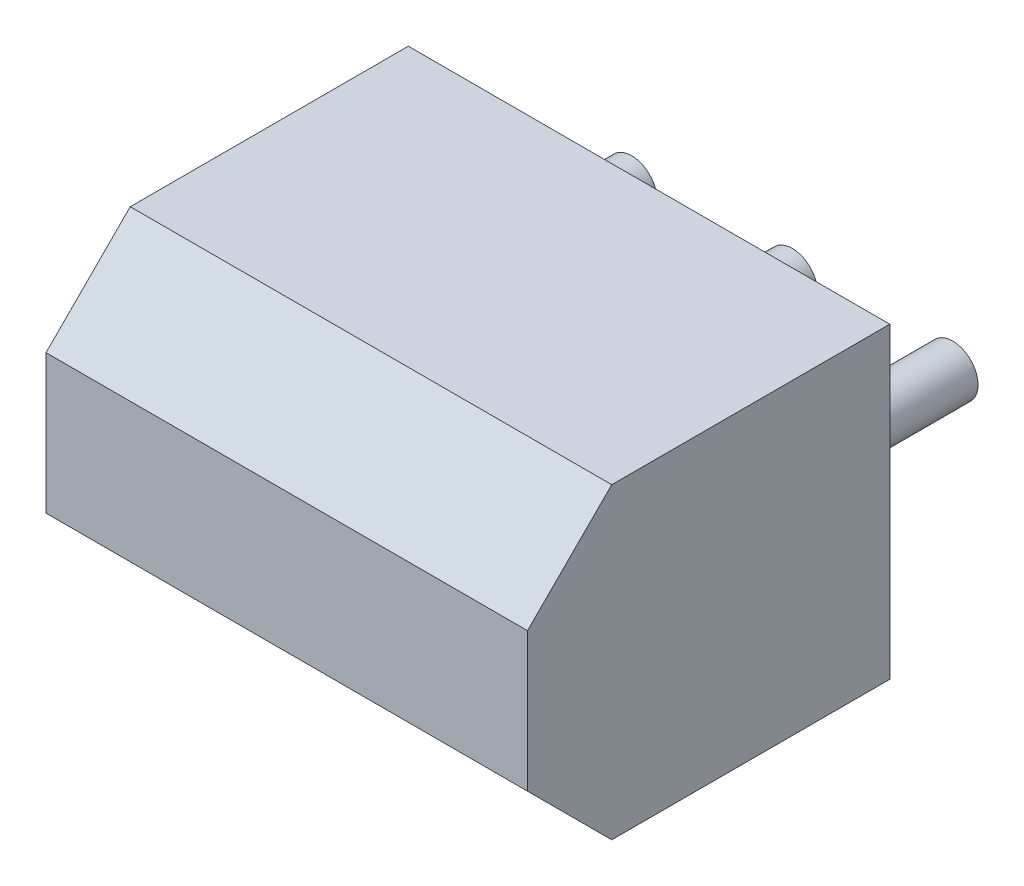
SolidWorks part; units mm, degrees
ref_plane "前视基准面" through (0, 0, 0) normal (0, 0, 1) x (1, 0, 0)
ref_plane "上视基准面" through (0, 0, 0) normal (0, 1, 0) x (1, 0, 0)
ref_plane "右视基准面" through (0, 0, 0) normal (1, 0, 0) x (0, 0, -1)
sketch "草图1" plane through (0, 0, 0) normal (0, 0, 1) x (1, 0, 0)
  line L1 (0, 0) -> (11.43, 0)
  line L2 (0, 0) -> (0, 7.3)
  line L3 (0, 7.3) -> (11.43, 7.3)
  line L4 (11.43, 0) -> (11.43, 7.3)
  dimension "D1" = 11.43
  dimension "D2" = 7.3
extrude "凸台-拉伸1" add sketch "草图1" along normal blind 8.6
chamfer "倒角1" distance 2 angle 45 2 edges at (5.715, 0, 8.6) (5.715, 7.3, 8.6)
sketch "草图2" plane through (0, 0, 0) normal (0, -1, 0) x (1, 0, 0)
  line L1 (4.965, 4.7244) -> (6.465, 4.7244)
  line L2 (4.965, 4.7244) -> (4.965, 2.4797)
  line L3 (4.965, 2.4797) -> (6.465, 2.4797)
  line L4 (6.465, 4.7244) -> (6.465, 2.4797)
  line L5 (5.715, 0) -> (5.715, 12.0535) construction
  line L6 (0, 0) -> (11.43, 0) construction
  line L7 (5.715, 4.7244) -> (5.715, 1.5061) construction
  dimension "D1" = 0
  dimension "D2" = 1.5
extrude "切除-拉伸1" cut sketch "草图2" against normal blind 0.5
pattern_linear "阵列(线性)1" count 2 spacing 3.81 along (1, 0, 0) count 2 spacing 3.81 along (-1, 0, 0) of "切除-拉伸1"
sketch "草图3" plane through (0, 0, 0) normal (0, 0, -1) x (-1, 0, 0)
  line L0 (-11.43, 3.7) -> (2.0184, 3.7) construction
  line L1 (-11.43, 0) -> (-11.43, 7.3) construction
  line L2 (-11.43, 7.3) -> (0, 7.3) construction
  line L3 (-5.715, 7.3) -> (-5.715, -1.5587) construction
  circle A0 centre (-5.715, 3.7) radius 0.6
  dimension "D2" = 1.2
  dimension "D1" = 3.6
  dimension "D3" = 0
extrude "凸台-拉伸2" add sketch "草图3" along normal blind 3.4
pattern_linear "阵列(线性)2" count 2 spacing 3.81 along (-1, 0, 0) count 2 spacing 3.81 along (1, 0, 0) of "凸台-拉伸2"
pattern_linear "阵列(线性)3" count 2 spacing 3.81 along (-1, 0, 0) of "凸台-拉伸2"
